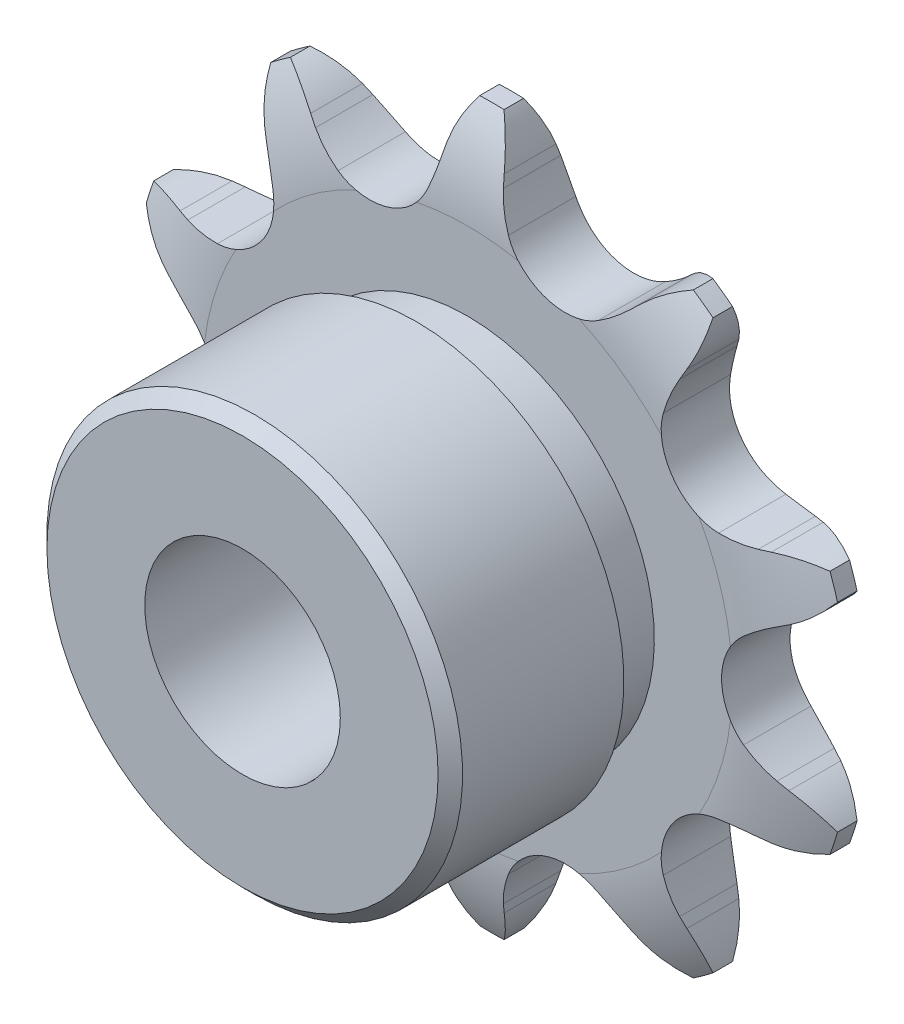
SolidWorks part; units mm, degrees
ref_plane "Front Plane" through (0, 0, 0) normal (0, 0, 1) x (1, 0, 0)
ref_plane "Top Plane" through (0, 0, 0) normal (0, 1, 0) x (1, 0, 0)
ref_plane "Right Plane" through (0, 0, 0) normal (1, 0, 0) x (0, 0, -1)
sketch "Sketch0" plane through (0, 0, 0) normal (0, 0, 1) x (1, 0, 0)
  line L0 (4, -12.3107) -> (0, 0) construction
  line L1 (0, 0) -> (10.4721, -7.6085) construction
  line L2 (0, 0) -> (-4, -12.3107) construction
  line L3 (4, -12.3107) -> (10.4721, -7.6085) construction
  line L4 (4, -12.3107) -> (-4, -12.3107) construction
  line L5 (6.7522, -11.2745) -> (6.4407, -10.9799)
  line L6 (4, -12.3107) -> (0, -13.6104) construction
  line L7 (1.1643, -13.0901) -> (1.2432, -12.6687)
  line L8 (0, -12.3107) -> (0, -14.7107) construction
  line L9 (5.3137, -10.1244) -> (1.9398, -15.7394) construction
  line L10 (0, 0) -> (0, -12.3107) construction
  line L11 (6.4407, -10.9799) -> (1.9398, -15.7394) construction
  line L12 (0, -14.7107) -> (0, -15.3022) construction
  line L13 (9.6631, -8.1962) -> (6.7522, -11.2745) construction
  circle A0 centre (0, 0) radius 14.7107 construction
  circle A1 centre (0, 0) radius 12.9443 construction
  arc A2 (-4.0031, -16.4269) -> (12.8941, -10.9367) centre (0, 0) ccw
  circle A3 centre (0, 0) radius 15.3022 construction
  circle A4 centre (4, -12.3107) radius 2.5 construction
  arc A7 (5.3137, -10.1244) -> (1.6522, -11.3141) centre (4, -12.3107) ccw
  circle A8 centre (4, -12.3107) radius 2.5506 construction
  arc A9 (6.7522, -11.2745) -> (12.8941, -10.9367) centre (9.6631, -8.1962) ccw
  arc A10 (6.4407, -10.9799) -> (5.3137, -10.1244) centre (1.9398, -15.7394) ccw
  arc A11 (1.1643, -13.0901) -> (-4.0031, -16.4269) centre (-3, -12.3107) cw
  arc A12 (1.2432, -12.6687) -> (1.6522, -11.3141) centre (7.682, -13.8737) cw
  dimension "D1" = 2.5506
  dimension "Dr" = 5
  dimension "Ds" = 5.1012
  dimension "R" = 2.5506
  dimension "Pitch" = 8
  dimension "A" = 41
  dimension "360/N" = 36
  dimension "B" = 12.4
  dimension "ab" = 7
  dimension "J" = 2.4
  dimension "ac" = 4
sketch "Sketch1" plane through (0, 0, 0) normal (1, 0, 0) x (0, 0, -1)
  line L0 (1.4, 0) -> (-1.4, 0)
  line L1 (-1.4, 0) -> (-1.4, 10.8378)
  line L2 (-1.4, 12.9443) -> (0, 12.9443) construction
  line L3 (-0.4, 14.7107) -> (0.4, 14.7107)
  line L5 (1.4, 10.8378) -> (1.4, 0)
  line L7 (0, 14.7107) -> (0, 0) construction
  line L8 (-1.4, 10.8378) -> (1.4, 10.8378) construction
  line L9 (0, 14.7107) -> (0, -14.7107) construction
  line L10 (-1.4, 10.8378) -> (-1.4, 14.7107) construction
  line L11 (-1.4, 14.7107) -> (-0.4, 14.7107) construction
  line L12 (0.4, 14.7107) -> (1.4, 14.7107) construction
  line L13 (1.4, 14.7107) -> (1.4, 10.8378) construction
  line L14 (0, 0) -> (-6.4008, 0) construction
  line L15 (-1.4, 12.9443) -> (-1.4, 7.6443) construction
  line L22 (1.4, 0) -> (-10.6, 0) construction
  line L24 (-1.4, 0) -> (-1.4, 7.6443) construction
  arc A0 (-0.4, 14.7107) -> (-1.4, 10.8378) centre (6.6, 10.8378) ccw
  arc A1 (0.4, 14.7107) -> (1.4, 10.8378) centre (-6.6, 10.8378) cw
  dimension "R" = 8
  dimension "t" = 2.8
  dimension "C" = 1
  dimension "A" = 3.873
  dimension "K" = 6.4008
  dimension "Width" = 12
  dimension "H" = 5.3
revolve "Revolve1" add sketch "Sketch1" angle 360 about L0
extrude "Cut-Extrude1" cut sketch "Sketch0" against normal through all and the other way through all
pattern_circular "CirPattern1" count 10 over 360 about axis through (0, 0, 0) along (0, 0, 1) of "Cut-Extrude1"
sketch "Sketch2" plane through (0, 0, 0) normal (0, 0, 1) x (1, 0, 0)
  circle A0 centre (0, 0) radius 4 construction
  circle A1 centre (0, 0) radius 8.5
  circle A2 centre (0, 0) radius 14.71 construction
  dimension "Bore" = 8
  dimension "Hub Dia." = 17
  dimension "OD" = 29.42
extrude "Boss-Extrude1" add sketch "Sketch2" along normal up to vertex (10.6 mm away) from surface at 1.4 starting at face at (0, 0, 1.4)
sketch "Sketch3" plane through (0, 0, 0) normal (0, 0, 1) x (1, 0, 0)
  circle A0 centre (0, 0) radius 4 construction
  circle A1 centre (0, 0) radius 4
extrude "Cut-Extrude2" cut sketch "Sketch3" along normal through all and the other way through all
sketch "Sketch4" plane through (0, 0, 0) normal (1, 0, 0) x (0, 0, -1)
  line L0 (-10.6, 8.5) -> (-10.6, 8)
  line L1 (-1.4, 14.7107) -> (-3.5, 14.7107)
  line L2 (-1.4, 14.7107) -> (-1.4, 7.6443)
  line L3 (-1.4, 7.6443) -> (-3.5, 7.6443)
  line L4 (-3.5, 14.7107) -> (-3.5, 7.6443)
  line L9 (-10.6, 8) -> (-10.1, 8.5)
  line L10 (-10.1, 8.5) -> (-10.6, 8.5)
  dimension "C" = 0.5
  dimension "D3" = 2.1
revolve "Cut-Revolve1" cut sketch "Sketch4" angle 360 about L22
sketch "Sketch5" plane through (0, 0, 0) normal (0, 0, 1) x (1, 0, 0)
  circle A0 centre (0, 0) radius 14.71 construction
  circle A1 centre (0, 0) radius 14.71
extrude "Cut-Extrude3" [suppressed] cut sketch "Sketch5" against normal through all and the other way through all flip side to cut
equation "\"360/N@Sketch0\" = 360/\"Teeth@CirPattern1\""
equation "\"Ds@Sketch0\" = 1.005 * \"Dr@Sketch0\" + ( 0.003 * 25.4 ) "
equation "\"R@Sketch0\" = 1/2 * \"Ds@Sketch0\""
equation "\"A@Sketch0\" = 35 +  ( 60 / \"Teeth@CirPattern1\" ) "
equation "\"B@Sketch0\" = 18 -  ( 56 / \"Teeth@CirPattern1\" )"
equation "\"ac@Sketch0\" = 0.8 * \"Dr@Sketch0\""
equation "\"ab@Sketch0\" = 1.4 * \"Dr@Sketch0\""
equation "\"J@Sketch0\" = 0.3 * \"Pitch@Sketch0\""
equation "\"D3@Sketch4\" = \"t@Sketch1\" * 3 / 4"
